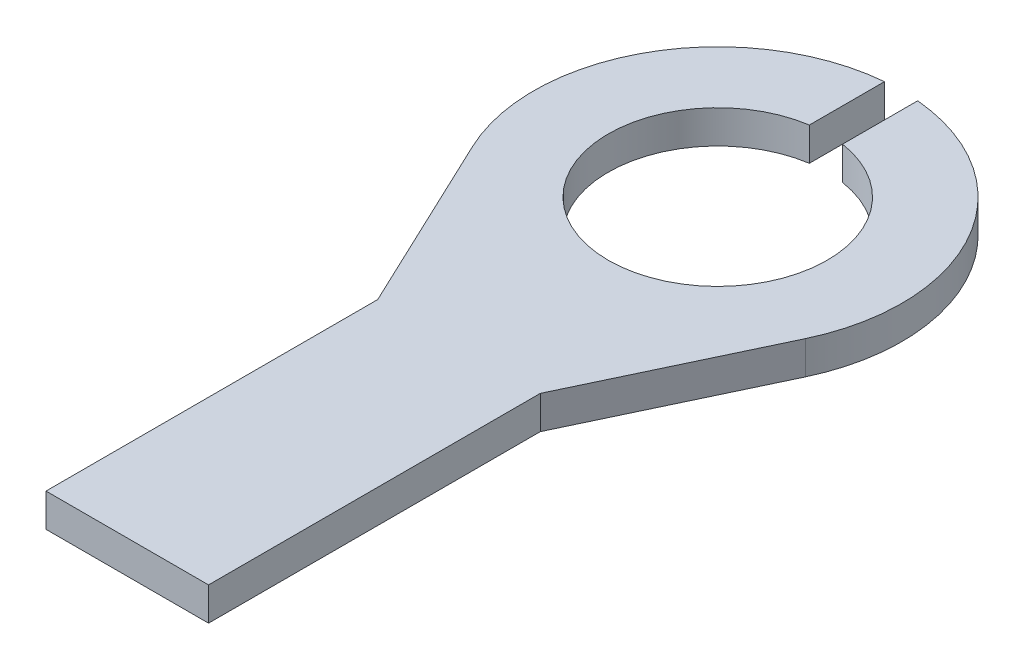
SolidWorks part; units mm, degrees
ref_plane "Front Plane" through (0, 0, 0) normal (0, 0, 1) x (1, 0, 0)
ref_plane "Top Plane" through (0, 0, 0) normal (0, 1, 0) x (1, 0, 0)
ref_plane "Right Plane" through (0, 0, 0) normal (1, 0, 0) x (0, 0, -1)
sketch "Sketch1" plane through (0, 0, 0) normal (0, 1, 0) x (1, 0, 0)
  line L0 (1.2743, -0.6028) -> (0.6223, -1.9812)
  line L1 (-1.2743, -0.6028) -> (-0.6223, -1.9812)
  line L2 (-0.6223, -1.2649) -> (-0.6223, -4.5212)
  line L3 (-0.6223, -4.5212) -> (0.6223, -4.5212)
  line L4 (0.6223, -4.5212) -> (0.6223, -1.2649)
  line L5 (-0.127, 1.404) -> (-0.127, 0.8285)
  line L6 (0.127, 1.404) -> (0.127, 0.8285)
  line L7 (-0.127, 1.1162) -> (0.127, 1.1162) construction
  circle A0 centre (0, 0) radius 0.8382
  circle A1 centre (0, 0) radius 1.4097
  point P14 (0, -4.5212)
  dimension "D1" = 1.6764
  dimension "D2" = 2.8194
  dimension "D3" = 1.2446
  dimension "D4" = 4.5212
  dimension "D5" = 2.54
  dimension "D6" = 2.54
  dimension "D7" = 0.254
extrude "Boss-Extrude1" add sketch "Sketch1" along normal blind 0.254 contours A1 L6 A0 L5 | A1 L4 L0 | A1 L2 L3 L4 | A1 L1 L2
equation "\"D4@Sketch1\"=0.145in + \"D1@Sketch1\"/2"
equation "\"D6@Sketch1\"=\"D5@Sketch1\""
